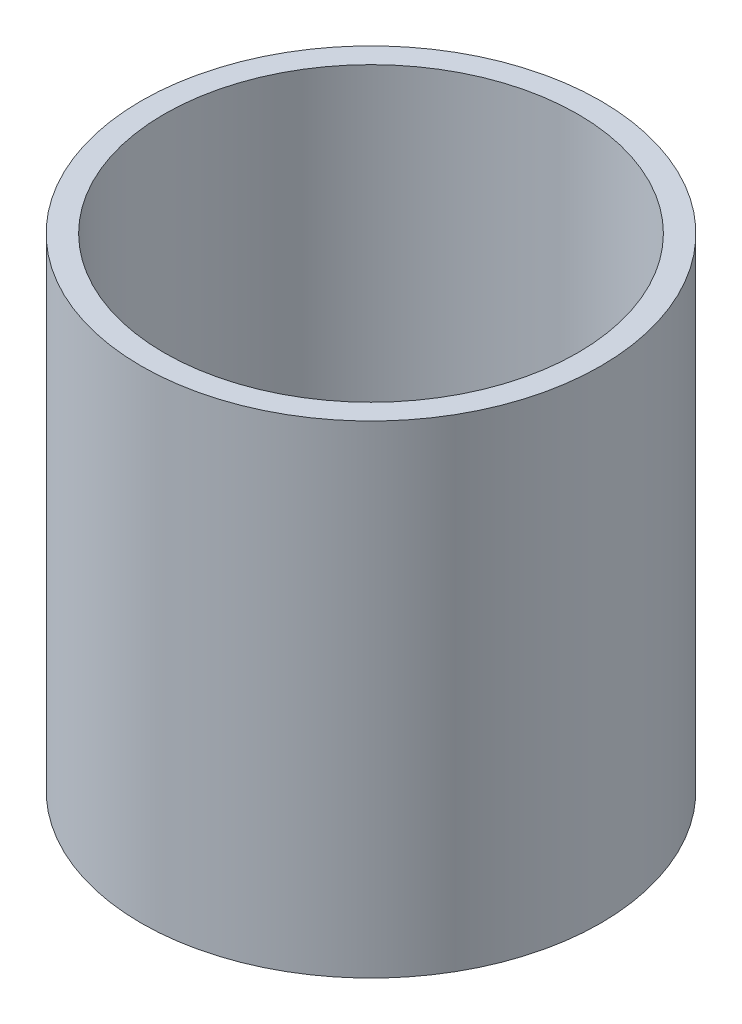
SolidWorks part; units mm, degrees
ref_plane "前视基准面" through (0, 0, 0) normal (0, 0, 1) x (1, 0, 0)
ref_plane "上视基准面" through (0, 0, 0) normal (0, 1, 0) x (1, 0, 0)
ref_plane "右视基准面" through (0, 0, 0) normal (1, 0, 0) x (0, 0, -1)
sketch "草图1" plane through (0, 0, 0) normal (0, 1, 0) x (1, 0, 0)
  circle A0 centre (0, 0) radius 9
  circle A1 centre (0, 0) radius 10
  dimension "D1" = 18
  dimension "D2" = 20
extrude "凸台-拉伸1" add sketch "草图1" along normal blind 21
